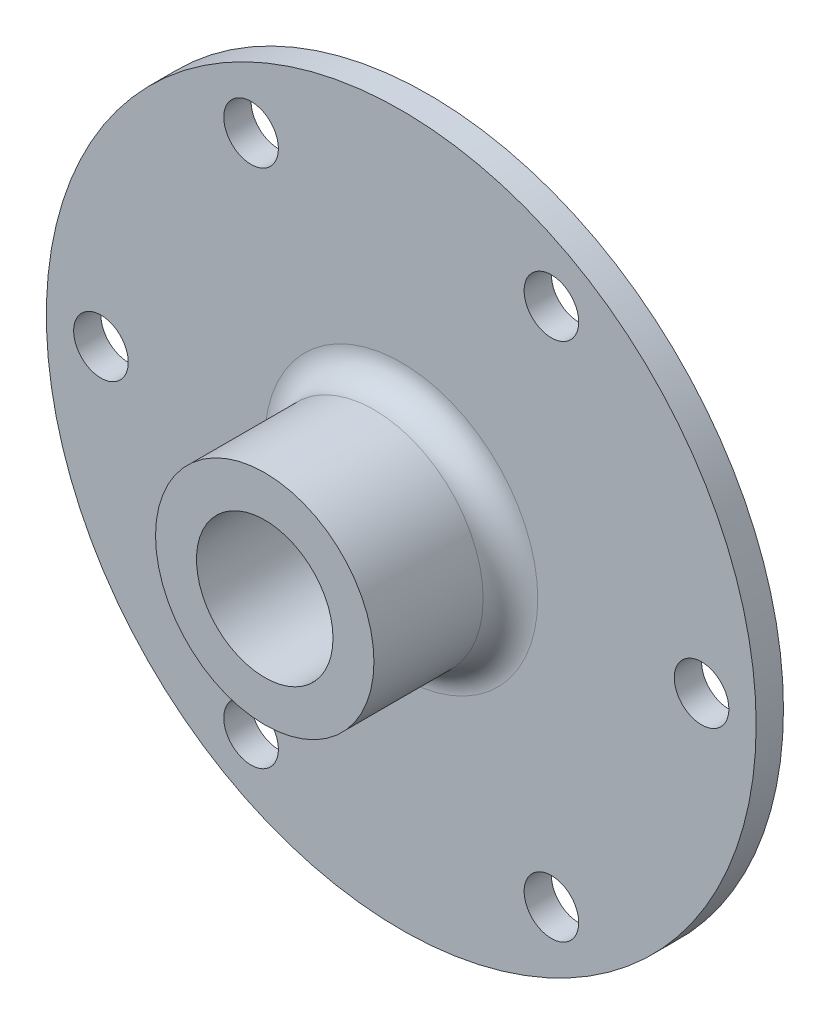
SolidWorks part; units mm, degrees
material "AISI 1020"
ref_plane "Front Plane" through (0, 0, 0) normal (0, 0, 1) x (1, 0, 0)
ref_plane "Top Plane" through (0, 0, 0) normal (0, 1, 0) x (1, 0, 0)
ref_plane "Right Plane" through (0, 0, 0) normal (1, 0, 0) x (0, 0, -1)
sketch "Sketch1" plane through (0, 0, 0) normal (1, 0, 0) x (0, 0, -1)
  line L0 (-19.05, 0) -> (0, 0)
  line L2 (0, 0) -> (0, 41.275)
  line L3 (0, 41.275) -> (-3.175, 41.275)
  line L4 (-3.175, 12.7) -> (-3.175, 41.275)
  line L6 (-19.05, 12.7) -> (-3.175, 12.7)
  line L7 (-19.05, 12.7) -> (-19.05, 0)
  dimension "D1" = 41.275
  dimension "D2" = 3.175
  dimension "D3" = 19.05
  dimension "D4" = 12.7
revolve "Flange Base" add sketch "Sketch1" angle 360 about L0
sketch "Sketch2" plane through (0, 0, 19.05) normal (0, 0, 1) x (1, 0, 0)
  circle A0 centre (0, 0) radius 7.9375
  dimension "D1" = 15.875
extrude "Cut-Extrude1" cut sketch "Sketch2" against normal through all
sketch "Sketch3" plane through (0, 0, 3.175) normal (0, 0, 1) x (1, 0, 0)
  line L0 (0, 0) -> (34.925, 0) construction
  circle A0 centre (34.925, 0) radius 3.175
  dimension "D2" = 6.35
  dimension "D1" = 34.925
extrude "Cut-Extrude2" cut sketch "Sketch3" against normal through all
pattern_circular "CirPattern1" count 6 over 360 about axis through (0, 0, 0) along (0, 0, 1) of "Cut-Extrude2"
fillet "Fillet1" radius 3.175 1 edges at (12.7, 0, 3.175)
